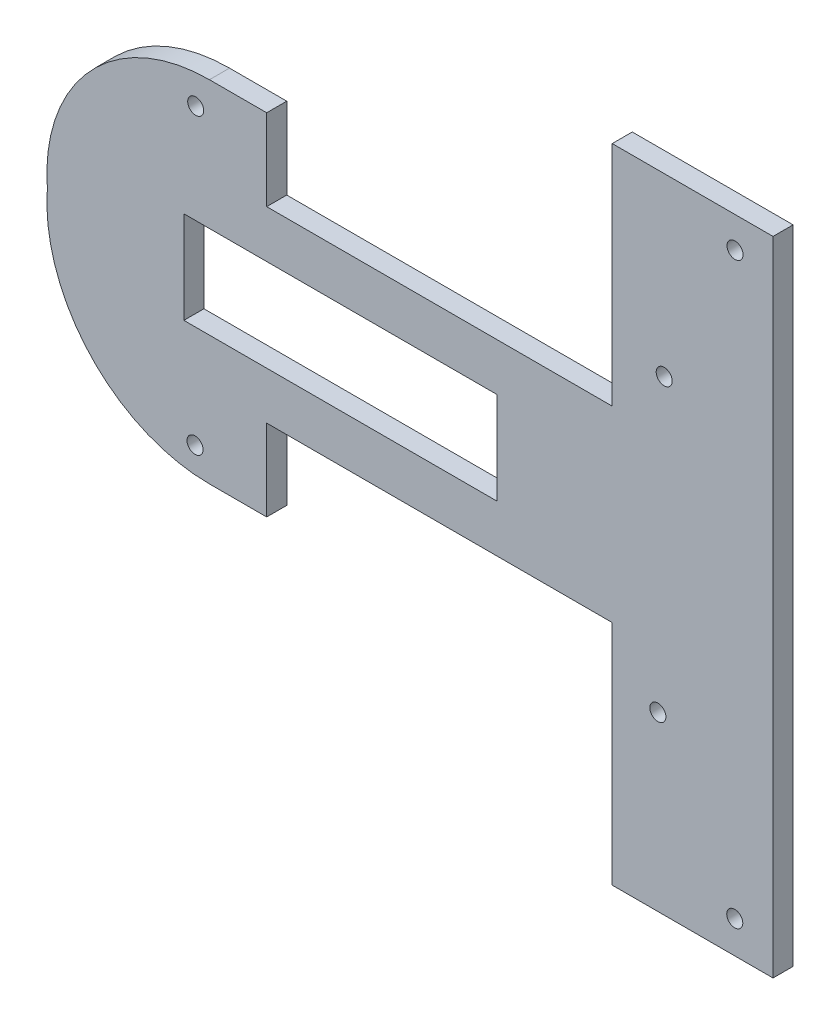
SolidWorks part; units mm, degrees
ref_plane "Plan de face" through (0, 0, 0) normal (0, 0, 1) x (1, 0, 0)
ref_plane "Plan de dessus" through (0, 0, 0) normal (0, 1, 0) x (1, 0, 0)
ref_plane "Plan de droite" through (0, 0, 0) normal (1, 0, 0) x (0, 0, -1)
sketch "Esquisse1" plane through (0, 0, 0) normal (0, 0, 1) x (1, 0, 0)
  line L45 (0, 80) -> (-40.0634, 80)
  line L46 (-40.0634, 80) -> (-40.0634, 43.608)
  line L51 (-140.4048, 43.608) -> (-126.1447, 43.608)
  line L52 (-126.1447, 43.608) -> (-126.1447, 23.3472)
  line L53 (-126.1447, 23.3472) -> (-40.0634, 23.3472)
  line L54 (-40.0634, 23.3472) -> (-40.0634, 43.608)
  line L56 (0, -80) -> (0, 80)
  line L57 (-40.0634, -80) -> (-40.0634, -43.608)
  line L58 (0, -80) -> (-40.0634, -80)
  line L59 (-40.0634, -23.3472) -> (-40.0634, -43.608)
  line L60 (-126.1447, -23.3472) -> (-40.0634, -23.3472)
  line L61 (-126.1447, -43.608) -> (-126.1447, -23.3472)
  line L62 (-140.4048, -43.608) -> (-126.1447, -43.608)
  arc A0 (-140.4048, 43.608) -> (-180.7891, 0) centre (-140.4048, 3.1046) ccw
  circle A3 centre (-143.8294, 36.2066) radius 2
  circle A4 centre (-27.1131, 36.2066) radius 2
  circle A7 centre (-9.4671, 72.2918) radius 2
  circle A8 centre (-9.538, -71.9475) radius 2
  circle A9 centre (-28.6903, -37.0228) radius 2
  circle A10 centre (-143.9947, -37.0228) radius 2
  arc A11 (-140.4048, -43.608) -> (-180.7891, 0) centre (-140.4048, -3.1046) cw
extrude "Boss.-Extru.2" add sketch "Esquisse1" along normal blind 5
sketch "Esquisse2" plane through (0, 0, 5) normal (0, 0, 1) x (1, 0, 0)
  line L0 (-146.7768, -11.5) -> (-146.7768, 11.5)
  line L1 (-180.7891, 0) -> (0, 0) construction
  line L2 (-146.7768, 11.5) -> (-68.7768, 11.5)
  line L3 (-68.7768, 11.5) -> (-68.7768, -11.5)
  line L4 (-146.7768, -11.5) -> (-68.7768, -11.5)
  point P7 (-68.7768, 0)
  point P8 (-146.7768, 0)
extrude "Enlèv. mat.-Extru.2" cut sketch "Esquisse2" against normal blind 5
